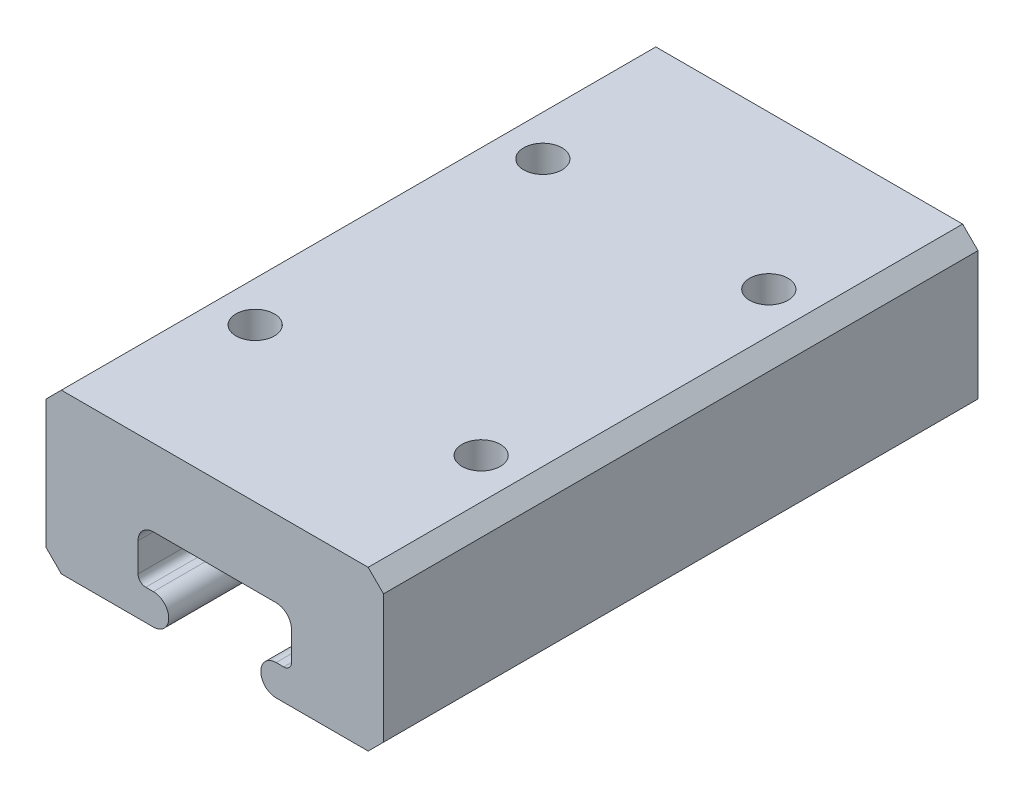
SolidWorks part; units mm, degrees
ref_plane "Front Plane" through (0, 0, 0) normal (0, 0, 1) x (1, 0, 0)
ref_plane "Top Plane" through (0, 0, 0) normal (0, 1, 0) x (1, 0, 0)
ref_plane "Right Plane" through (0, 0, 0) normal (1, 0, 0) x (0, 0, -1)
sketch "Sketch1" plane through (0, 0, 0) normal (0, 0, 1) x (1, 0, 0)
  line L0 (0, 8.75) -> (0, -8.75) construction
  line L3 (-8, 8.75) -> (8, 8.75)
  line L5 (-10, -8.75) -> (10, 8.75) construction
  line L6 (-10, 8.75) -> (10, -8.75) construction
  line L7 (0, 0) -> (-19.1226, 0) construction
  line L8 (-8, 2) -> (-9, 2)
  line L9 (-8, -2) -> (-9, -2)
  line L10 (-10, 3) -> (-10, 6.75)
  line L11 (8, -2) -> (9, -2)
  line L12 (8, 2) -> (9, 2)
  line L13 (10, 3) -> (10, 6.75)
  line L14 (0, 8.75) -> (0, 28.75) construction
  line L15 (0, 18.75) -> (22, 18.75) construction
  line L16 (-22, 18.75) -> (22, 18.75)
  line L17 (9, -2) -> (22, -2)
  line L18 (22, -2) -> (22, 18.75)
  line L19 (-9, -2) -> (-22, -2)
  line L20 (-22, -2) -> (-22, 18.75)
  arc A0 (-8, -2) -> (-8, 2) centre (-8, 0) ccw
  arc A3 (10, 6.75) -> (8, 8.75) centre (8, 6.75) ccw
  arc A4 (-8, 8.75) -> (-10, 6.75) centre (-8, 6.75) ccw
  arc A6 (-9, 2) -> (-10, 3) centre (-9, 3) cw
  arc A8 (8, -2) -> (8, 2) centre (8, 0) cw
  arc A9 (9, 2) -> (10, 3) centre (9, 3) ccw
  point P0 (0, 0)
  point P32 (-10, 2)
  dimension "D5" = 1
  dimension "D1" = 17.5
  dimension "D2" = 20
  dimension "D6" = 22
  dimension "D7" = 10
extrude "Boss-Extrude2" add sketch "Sketch1" along normal blind 77.5
chamfer "Chamfer1" distance 2 angle 45 4 edges at (-22, -2, 38.75) (22, -2, 38.75) (-22, 18.75, 38.75) (22, 18.75, 38.75)
sketch "Sketch2" plane through (0, 18.75, 0) normal (0, 1, 0) x (1, 0, 0)
  line L0 (14.7287, -77.5) -> (14.7287, 0) construction
  line L1 (20, -77.5) -> (-20, -77.5) construction
  line L2 (20, 0) -> (-20, 0) construction
  line L3 (0, 0) -> (0, -77.5) construction
  circle A0 centre (14.7287, -57.5) radius 2.5
  circle A1 centre (14.7287, -20) radius 2.5
  circle A2 centre (-14.7287, -57.5) radius 2.5
  circle A3 centre (-14.7287, -20) radius 2.5
  dimension "D1" = 20
  dimension "D2" = 20
extrude "Cut-Extrude1" cut sketch "Sketch2" against normal blind 7
